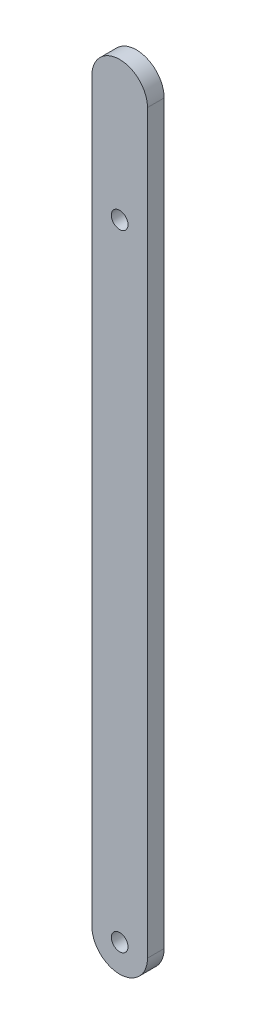
SolidWorks part; units mm, degrees
ref_plane "Front Plane" through (0, 0, 0) normal (0, 0, 1) x (1, 0, 0)
ref_plane "Top Plane" through (0, 0, 0) normal (0, 1, 0) x (1, 0, 0)
ref_plane "Right Plane" through (0, 0, 0) normal (1, 0, 0) x (0, 0, -1)
sketch "Sketch1" plane through (0, 0, 0) normal (0, 0, 1) x (1, 0, 0)
  line L0 (0, 0) -> (0, 225) construction
  line L1 (-10, 0) -> (-10, 225)
  line L2 (10, 0) -> (10, 225)
  arc A0 (-10, 0) -> (10, 0) centre (0, 0) ccw
  arc A1 (10, 225) -> (-10, 225) centre (0, 225) ccw
  point P3 (0, 112.5)
  dimension "D1" = 10
  dimension "D2" = 225
extrude "Boss-Extrude1" add sketch "Sketch1" along normal blind 6
sketch "Sketch2" plane through (0, 0, 6) normal (0, 0, 1) x (1, 0, 0)
  circle A0 centre (0, 225) radius 3
  circle A1 centre (0, 0) radius 3
  dimension "D1" = 6
extrude "Cut-Extrude1" cut sketch "Sketch2" against normal through all
sketch "Sketch3" plane through (0, 0, 6) normal (0, 0, 1) x (1, 0, 0)
  line L0 (-10, 225) -> (-10, 265)
  line L1 (10, 225) -> (10, 265)
  arc A0 (10, 265) -> (-10, 265) centre (0, 265) ccw
  arc A1 (10, 225) -> (-10, 225) centre (0, 225) ccw construction
  arc A2 (10, 225) -> (-10, 225) centre (0, 225) ccw
  dimension "D1" = 40
extrude "Boss-Extrude2" add sketch "Sketch3" against normal blind 6
